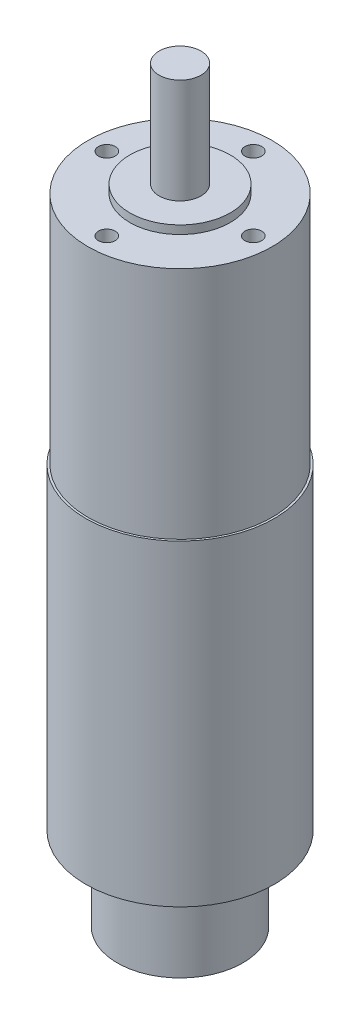
SolidWorks part; units mm, degrees
ref_plane "Front Plane" through (0, 0, 0) normal (0, 0, 1) x (1, 0, 0)
ref_plane "Top Plane" through (0, 0, 0) normal (0, 1, 0) x (1, 0, 0)
ref_plane "Right Plane" through (0, 0, 0) normal (1, 0, 0) x (0, 0, -1)
sketch "Sketch1" plane through (0, 0, 0) normal (0, 1, 0) x (1, 0, 0)
  circle A0 centre (0, 0) radius 22.5
extrude "Boss-Extrude1" add sketch "Sketch1" along normal blind 75.7
sketch "Sketch2" plane through (0, 75.7, 0) normal (0, 1, 0) x (1, 0, 0)
  circle A0 centre (0, 0) radius 22
extrude "Boss-Extrude3" add sketch "Sketch2" along normal blind 56
sketch "Sketch3" plane through (0, 131.7, 0) normal (0, 1, 0) x (1, 0, 0)
  circle A0 centre (0, 0) radius 5
extrude "Boss-Extrude4" add sketch "Sketch3" along normal blind 27
sketch "Sketch5" plane through (0, 131.7, 0) normal (0, 1, 0) x (1, 0, 0)
  circle A0 centre (0, 17.5) radius 2
  dimension "D1" = 17.5
extrude "Cut-Extrude2" cut sketch "Sketch5" against normal blind 9
pattern_circular "CirPattern1" count 4 over 360 about axis through (0, 0, 0) along (0, 1, 0) of "Cut-Extrude2"
sketch "Sketch6" plane through (0, 131.7, 0) normal (0, 1, 0) x (1, 0, 0)
  circle A0 centre (0, 0) radius 12
extrude "Boss-Extrude5" add sketch "Sketch6" along normal blind 2
sketch "Sketch7" plane through (0, 0, 0) normal (0, -1, 0) x (1, 0, 0)
  circle A0 centre (0, 0) radius 15
extrude "Boss-Extrude6" add sketch "Sketch7" along normal blind 20
